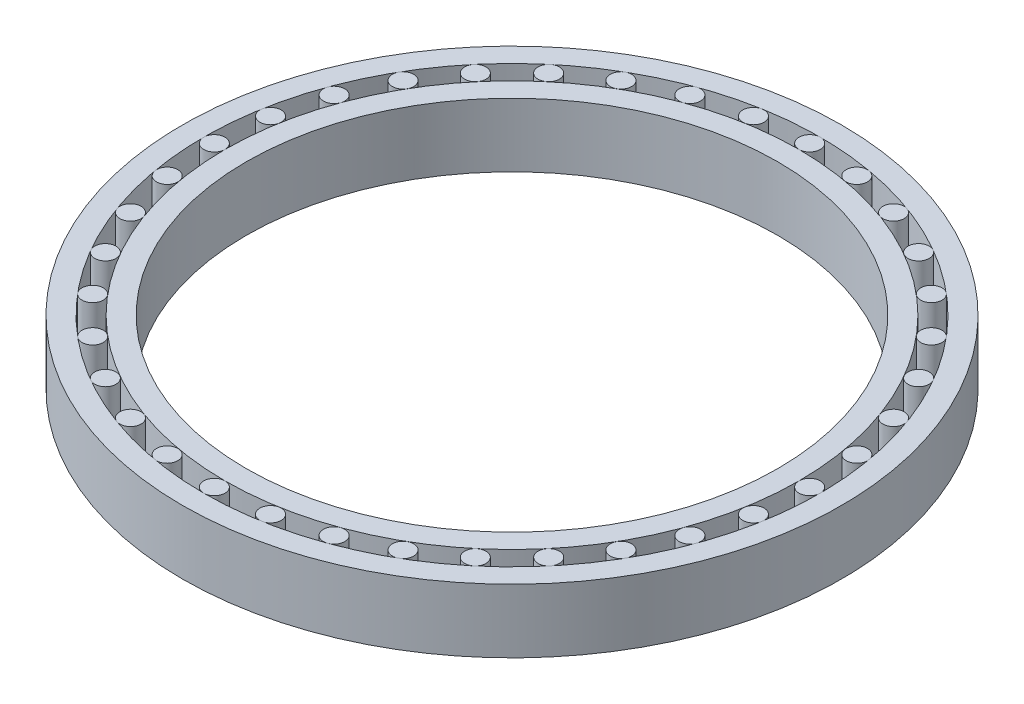
SolidWorks part; units mm, degrees
ref_plane "前视基准面" through (0, 0, 0) normal (0, 0, 1) x (1, 0, 0)
ref_plane "上视基准面" through (0, 0, 0) normal (0, 1, 0) x (1, 0, 0)
ref_plane "右视基准面" through (0, 0, 0) normal (1, 0, 0) x (0, 0, -1)
sketch "草图1" plane through (0, 0, 0) normal (0, 1, 0) x (1, 0, 0)
  circle A0 centre (0, 0) radius 25
  circle A1 centre (0, 0) radius 27
extrude "凸台-拉伸1" add sketch "草图1" along normal blind 6
sketch "草图2" plane through (0, 0, 0) normal (0, 1, 0) x (1, 0, 0)
  circle A0 centre (0, 0) radius 31
  circle A1 centre (0, 0) radius 29
extrude "凸台-拉伸2" add sketch "草图2" along normal blind 6 separate body
sketch "草图3" plane through (0, 0, 0) normal (0, 1, 0) x (1, 0, 0)
  line L0 (0, 0) -> (-27, 0) construction
  line L1 (-27, 0) -> (-29, 0) construction
  circle A0 centre (0, 0) radius 27 construction
  circle A1 centre (0, 0) radius 29 construction
  circle A2 centre (-28, 0) radius 1
extrude "凸台-拉伸3" add sketch "草图3" along normal blind 6 separate body
pattern_circular "阵列(圆周)25" count 36 every 10 about axis through (0, 0, 0) along (0, 1, 0) of bodies 104
